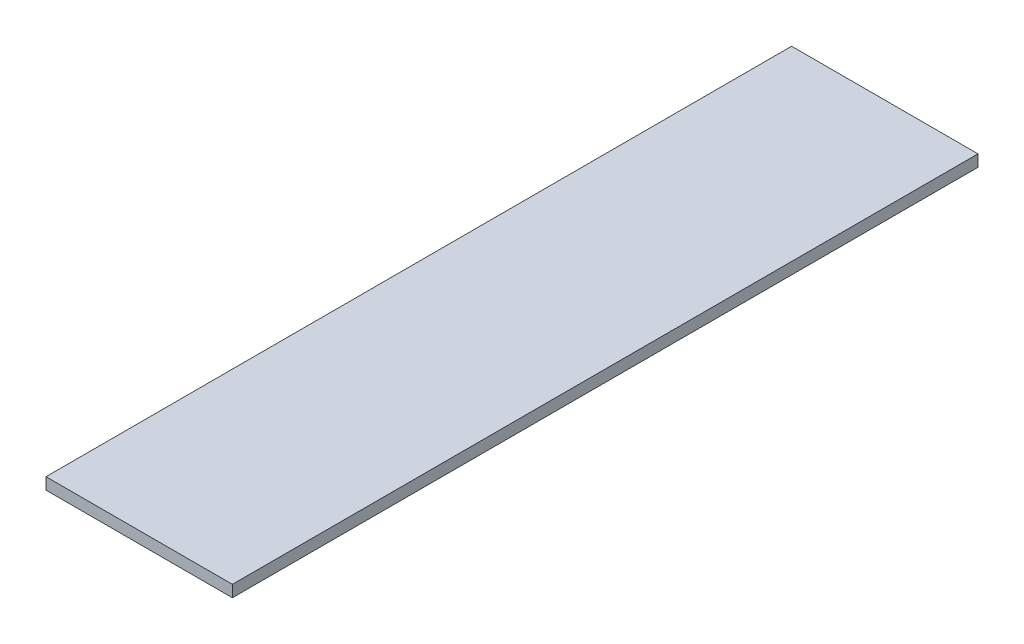
SolidWorks part; units mm, degrees
ref_plane "Front Plane" through (0, 0, 0) normal (0, 0, 1) x (1, 0, 0)
ref_plane "Top Plane" through (0, 0, 0) normal (0, 1, 0) x (1, 0, 0)
ref_plane "Right Plane" through (0, 0, 0) normal (1, 0, 0) x (0, 0, -1)
sketch "Sketch1" plane through (0, 0, 0) normal (0, 1, 0) x (1, 0, 0)
  line L1 (12.7, 50.8) -> (-12.7, 50.8)
  line L2 (12.7, 50.8) -> (12.7, -50.8)
  line L3 (12.7, -50.8) -> (-12.7, -50.8)
  line L4 (-12.7, 50.8) -> (-12.7, -50.8)
  line L5 (12.7, 50.8) -> (-12.7, -50.8) construction
  line L6 (12.7, -50.8) -> (-12.7, 50.8) construction
  point P0 (0, 0)
  dimension "D1" = 101.6
  dimension "D2" = 25.4
extrude "Boss-Extrude1" add sketch "Sketch1" along normal blind 1.5875
